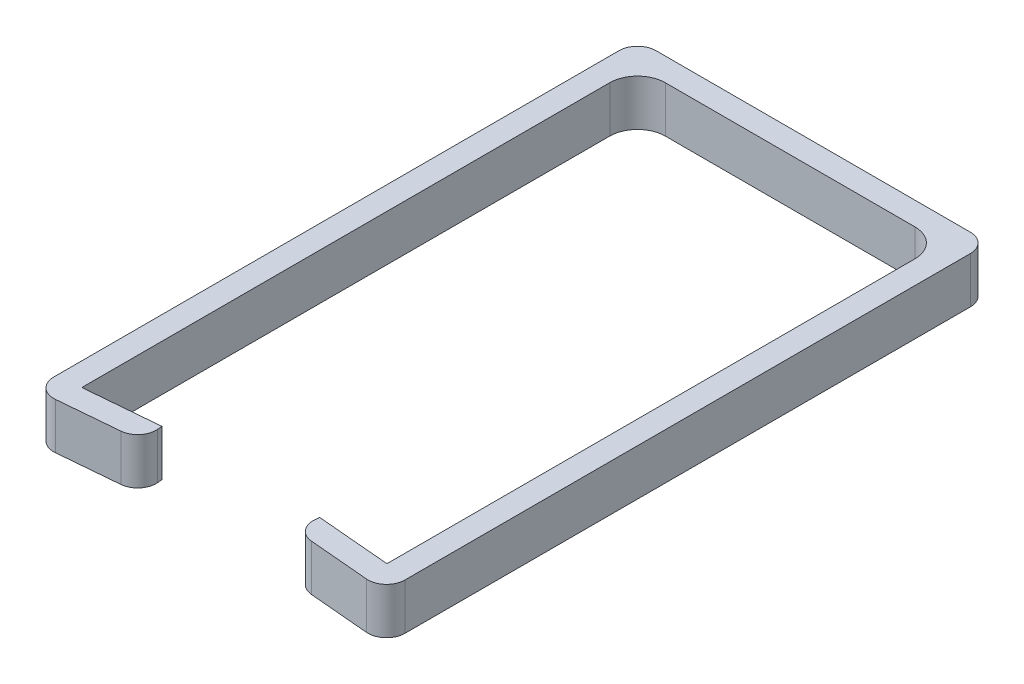
SolidWorks part; units mm, degrees
ref_plane "Front Plane" through (0, 0, 0) normal (0, 0, 1) x (1, 0, 0)
ref_plane "Top Plane" through (0, 0, 0) normal (0, 1, 0) x (1, 0, 0)
ref_plane "Right Plane" through (0, 0, 0) normal (1, 0, 0) x (0, 0, -1)
sketch "Sketch1" plane through (0, 0, 0) normal (0, 1, 0) x (1, 0, 0)
  line L0 (0, 0) -> (0, 59.6)
  line L1 (0, 59.6) -> (33, 59.6)
  line L2 (33, 59.6) -> (33, 0)
  line L3 (0, 0) -> (4, 0)
  line L4 (4, 0) -> (4, -2)
  line L5 (4, -2) -> (-2, -2)
  line L6 (-2, -2) -> (-2, 61.6)
  line L7 (-2, 61.6) -> (35, 61.6)
  line L8 (35, 61.6) -> (35, -2)
  line L9 (35, -2) -> (29, -2)
  line L10 (29, -2) -> (29, 0)
  line L11 (29, 0) -> (33, 0)
  dimension "D1" = 59.6
  dimension "D2" = 33
  dimension "D3" = 37
  dimension "D4" = 2
  dimension "D5" = 2
  dimension "D6" = 2
  dimension "D7" = 2
  dimension "D8" = 6
  dimension "D9" = 6
sketch "Sketch2" plane through (0, 0, 0) normal (0, 1, 0) x (1, 0, 0)
  line L0 (0, 0) -> (0, 60.1)
  line L1 (0, 60.1) -> (33, 60.1)
  line L2 (33, 60.1) -> (33, 0)
  line L3 (0, 0) -> (7.9696, 0.6972)
  line L4 (33, 0) -> (25.0304, 0.6972)
  line L5 (-2.5, -2.7283) -> (8.1874, -1.7932)
  line L6 (-2.5, -2.7283) -> (-2.5, 62.6)
  line L7 (-2.5, 62.6) -> (35.5, 62.6)
  line L8 (35.5, 62.6) -> (35.5, -2.7283)
  line L9 (35.5, -2.7283) -> (24.8126, -1.7932)
  line L10 (7.9696, 0.6972) -> (8.1874, -1.7932)
  line L11 (25.0304, 0.6972) -> (24.8126, -1.7932)
  dimension "D1" = 60.1
  dimension "D2" = 33
  dimension "D3" = 60.1
  dimension "D4" = 85
  dimension "D5" = 90
  dimension "D6" = 8
  dimension "D7" = 8
  dimension "D8" = 2.5
  dimension "D9" = 85
extrude "Boss-Extrude1" add sketch "Sketch2" along normal blind 5
fillet "Fillet1" radius 3 2 edges at (33, 2.5, -60.1) (0, 2.5, -60.1)
fillet "Fillet2" radius 2 6 edges at (-2.5, 2.5, 2.7283) (8.1874, 2.5, 1.7932) (24.8126, 2.5, 1.7932) (35.5, 2.5, 2.7283) (35.5, 2.5, -62.6) (-2.5, 2.5, -62.6)
